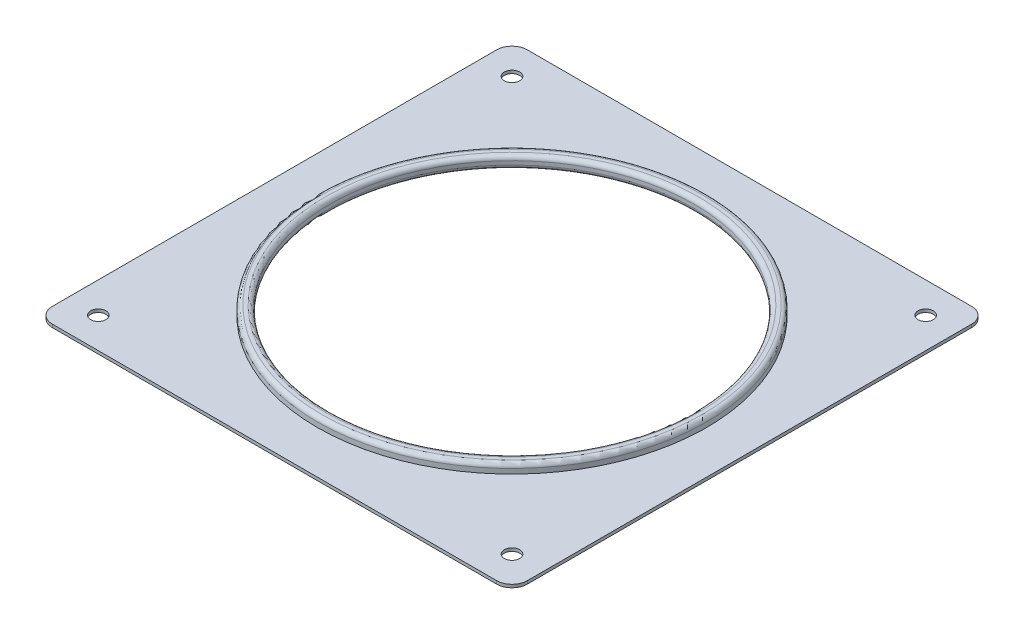
SolidWorks part; units mm, degrees
ref_plane "Front Plane" through (0, 0, 0) normal (0, 0, 1) x (1, 0, 0)
ref_plane "Top Plane" through (0, 0, 0) normal (0, 1, 0) x (1, 0, 0)
ref_plane "Right Plane" through (0, 0, 0) normal (1, 0, 0) x (0, 0, -1)
sketch "Sketch1" plane through (0, 0, 0) normal (0, 1, 0) x (1, 0, 0)
  line L1 (-72.5, -77.5) -> (72.5, -77.5)
  line L2 (-77.5, -72.5) -> (-77.5, 72.5)
  line L3 (-72.5, 77.5) -> (72.5, 77.5)
  line L4 (77.5, -72.5) -> (77.5, 72.5)
  line L5 (-77.5, -77.5) -> (77.5, 77.5) construction
  line L6 (-77.5, 77.5) -> (77.5, -77.5) construction
  line L7 (-67.5, -67.5) -> (67.5, -67.5) construction
  line L8 (-67.5, -67.5) -> (-67.5, 67.5) construction
  line L9 (-67.5, 67.5) -> (67.5, 67.5) construction
  line L10 (67.5, -67.5) -> (67.5, 67.5) construction
  line L11 (-67.5, -67.5) -> (67.5, 67.5) construction
  line L12 (-67.5, 67.5) -> (67.5, -67.5) construction
  circle A0 centre (0, 0) radius 59.5
  circle A1 centre (-67.5, 67.5) radius 2.5
  circle A2 centre (67.5, 67.5) radius 2.5
  circle A3 centre (67.5, -67.5) radius 2.5
  circle A4 centre (-67.5, -67.5) radius 2.5
  arc A5 (-77.5, -72.5) -> (-72.5, -77.5) centre (-72.5, -72.5) ccw
  arc A6 (72.5, -77.5) -> (77.5, -72.5) centre (72.5, -72.5) ccw
  arc A7 (77.5, 72.5) -> (72.5, 77.5) centre (72.5, 72.5) ccw
  arc A8 (-72.5, 77.5) -> (-77.5, 72.5) centre (-72.5, 72.5) ccw
  point P21 (0, 0)
  dimension "D1" = 155
  dimension "D2" = 119
  dimension "D3" = 5
  dimension "D5" = 5
  dimension "D4" = 4
  dimension "D6" = 135
extrude "Boss-Extrude1" add sketch "Sketch1" along normal blind 1
sketch "Sketch2" plane through (0, 1, 0) normal (0, 1, 0) x (1, 0, 0)
  circle A0 centre (0, 0) radius 59.5
  circle A1 centre (0, 0) radius 63.5
  dimension "D1" = 4
extrude "Boss-Extrude2" add sketch "Sketch2" along normal blind 3
fillet "Fillet1" radius 1.4 2 edges at (0, 4, 59.5) (0, 4, 63.5)
fillet "Fillet2" radius 1.4 1 edges at (0, 0, 59.5)
